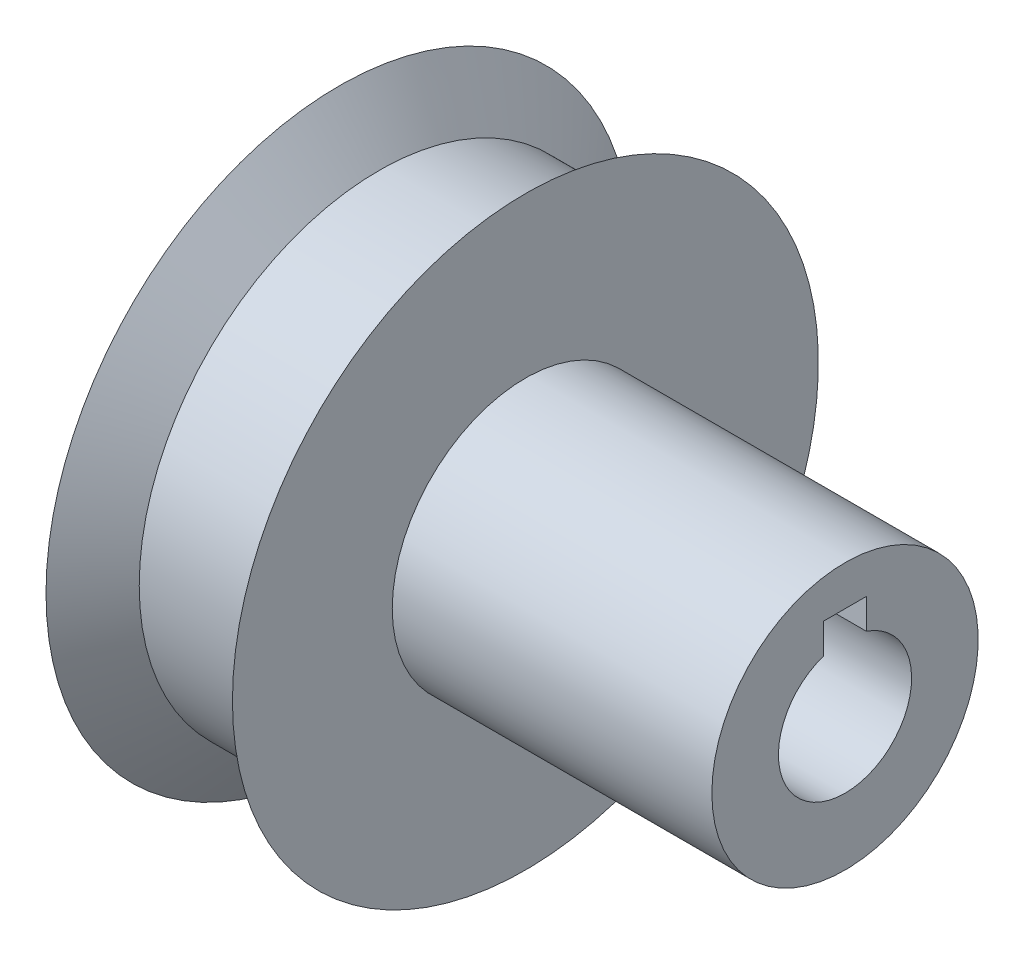
SolidWorks part; units mm, degrees
material "Gray Cast Iron"
ref_plane "Front Plane" through (0, 0, 0) normal (0, 0, 1) x (1, 0, 0)
ref_plane "Top Plane" through (0, 0, 0) normal (0, 1, 0) x (1, 0, 0)
ref_plane "Right Plane" through (0, 0, 0) normal (1, 0, 0) x (0, 0, -1)
sketch "Sketch1" plane through (0, 0, 0) normal (0, 1, 0) x (1, 0, 0)
  line L0 (0, 0) -> (1025.9988, 0) construction
  line L1 (95, 12.5) -> (95, 25)
  line L2 (7.5, 45) -> (0, 55)
  line L3 (95, 25) -> (35, 25)
  line L4 (35, 25) -> (35, 55)
  line L5 (0, 40) -> (25, 40)
  line L6 (0, 55) -> (0, 40)
  line L7 (7.5, 45) -> (28.0604, 45)
  line L8 (28.0604, 45) -> (35, 55)
  line L9 (25, 40) -> (25, 20)
  line L10 (25, 20) -> (50, 20)
  line L11 (95, 12.5) -> (50, 12.5)
  line L12 (50, 12.5) -> (50, 20)
revolve "Revolve1" add sketch "Sketch1" angle 360 about L0
sketch "Sketch3" plane through (95, 0, 0) normal (1, 0, 0) x (0, 0, -1)
  line L2 (0, 17.5) -> (-4, 17.5)
  line L3 (0, 17.5) -> (4, 17.5)
  line L4 (4, 17.5) -> (4, 10.1185)
  line L5 (4, 10.1185) -> (-4, 10.1185)
  line L6 (-4, 10.1185) -> (-4, 17.5)
extrude "Cut-Extrude2" cut sketch "Sketch3" against normal through all
